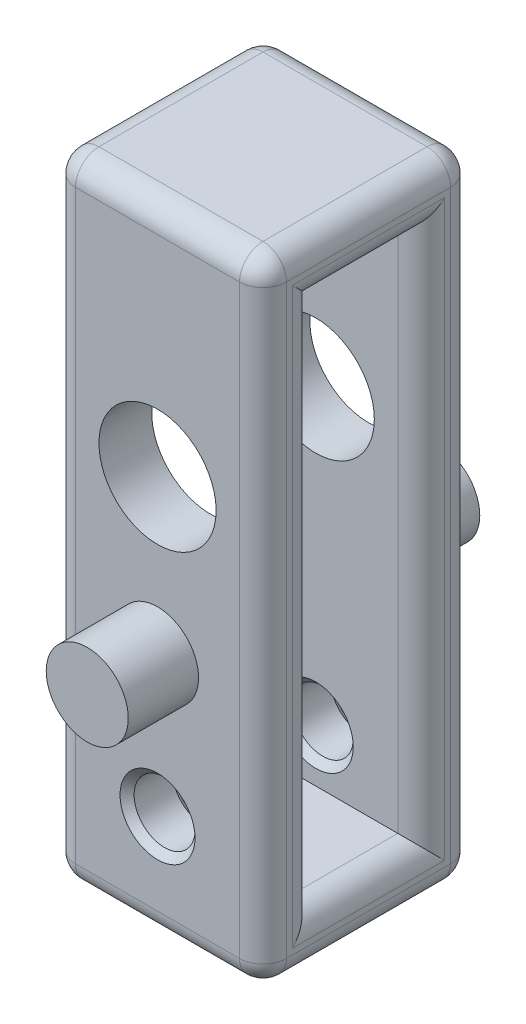
SolidWorks part; units mm, degrees
material "7075-O (SS)"
ref_plane "Front Plane" through (0, 0, 0) normal (0, 0, 1) x (1, 0, 0)
ref_plane "Top Plane" through (0, 0, 0) normal (0, 1, 0) x (1, 0, 0)
ref_plane "Right Plane" through (0, 0, 0) normal (1, 0, 0) x (0, 0, -1)
sketch "Sketch2" plane through (0, 0, 0) normal (0, 1, 0) x (1, 0, 0)
  line L1 (-45, -45) -> (45, -45)
  line L2 (-45, -45) -> (-45, 45)
  line L3 (-45, 45) -> (45, 45)
  line L4 (45, -45) -> (45, 45)
  line L5 (-45, -45) -> (45, 45) construction
  line L6 (-45, 45) -> (45, -45) construction
  point P0 (0, 0)
  dimension "D1" = 90
  dimension "D2" = 90
extrude "Boss-Extrude1" add sketch "Sketch2" along normal blind 270
sketch "Sketch3" plane through (45, 0, 0) normal (1, 0, 0) x (0, 0, -1)
  line L0 (-22.5, 22.5) -> (22.5, 22.5)
  line L1 (22.5, 22.5) -> (22.5, 247.5)
  line L2 (22.5, 247.5) -> (-22.5, 247.5)
  line L3 (-22.5, 247.5) -> (-22.5, 22.5)
  line L4 (-45, 0) -> (45, 0)
  line L5 (45, 0) -> (45, 270)
  line L6 (45, 270) -> (-45, 270)
  line L7 (-45, 270) -> (-45, 0)
  line L8 (-45, 0) -> (45, 0)
  line L9 (45, 0) -> (45, 270)
  line L10 (45, 270) -> (-45, 270)
  line L11 (-45, 270) -> (-45, 0)
  dimension "D2" = 45
  dimension "D1" = 0
extrude "Cut-Extrude1" cut sketch "Sketch3" against normal through all contours L0 L1 L2 L3
sketch "Sketch4" plane through (0, 0, 45) normal (0, 0, 1) x (1, 0, 0)
  circle A0 centre (0, 170.5) radius 25
  dimension "D1" = 50
  dimension "D2" = 148
extrude "Crank shaft hole" cut sketch "Sketch4" against normal blind 90
sketch "Sketch5" plane through (0, 0, 45) normal (0, 0, 1) x (1, 0, 0)
  circle A0 centre (0, 45) radius 13
  dimension "D1" = 26
  dimension "D2" = 22.5
extrude "Cut-Extrude3" cut sketch "Sketch5" against normal blind 90
chamfer "Chamfer1" distance 3 angle 45 4 edges at (13, 45, 22.5) (-13, 45, -22.5) (13, 45, -45) (13, 45, 45)
sketch "Sketch6" plane through (0, 0, 45) normal (0, 0, 1) x (1, 0, 0)
  circle A0 centre (0, 105) radius 17.5
  circle A1 centre (0, 45) radius 13 construction
  dimension "D1" = 35
  dimension "D2" = 60
extrude "Boss-Extrude2" add sketch "Sketch6" along normal blind 30
mirror "Mirror1" about plane through (0, 0, 0) normal (0, 0, 1) of "Boss-Extrude2"
fillet "Fillet1" radius 10 20 edges at (0, 270, 45) (0, 270, -45) (-45, 135, -45) (-45, 270, 0) (-45, 135, 45) (-45, 135, -22.5) (-45, 22.5, 0) (-45, 135, 22.5) (-45, 247.5, 0) (45, 135, 45) (45, 270, 0) (45, 135, -45) (45, 135, -22.5) (45, 247.5, 0) (45, 135, 22.5) (45, 22.5, 0) (0, 0, -45) (-45, 0, 0) (0, 0, 45) (45, 0, 0)
